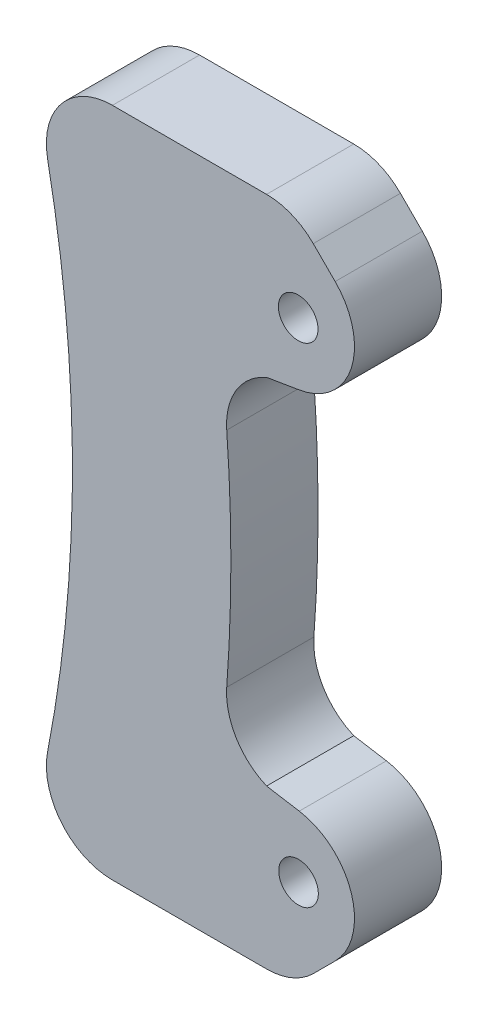
SolidWorks part; units mm, degrees
ref_plane "Front Plane" through (0, 0, 0) normal (0, 0, 1) x (1, 0, 0)
ref_plane "Top Plane" through (0, 0, 0) normal (0, 1, 0) x (1, 0, 0)
ref_plane "Right Plane" through (0, 0, 0) normal (1, 0, 0) x (0, 0, -1)
sketch "Model" plane through (0, 0, 0) normal (0, 0, 1) x (1, 0, 0)
  line L0 (0.4035, -13.81) -> (-2.0711, -13.4)
  line L1 (1.4645, -23.9355) -> (3.1217, -22.2783)
  line L2 (3.1217, 22.2783) -> (1.4645, 23.9355)
  line L3 (-2.0711, 13.4) -> (0.4035, 13.81)
  line L4 (-13.744, -25.4) -> (-2.0711, -25.4)
  line L5 (-2.0711, 25.4) -> (-13.744, 25.4)
  circle A0 centre (0.325, 18.5) radius 1.5
  circle A1 centre (0.3485, -18.5) radius 1.5
  arc A2 (-2.0711, 13.4) -> (-5.0872, 8.4333) centre (-0.101, 8.8045) ccw
  arc A3 (-5.0872, -8.4333) -> (-5.0872, 8.4333) centre (-118.3738, 0) ccw
  arc A4 (-5.0872, -8.4333) -> (-2.0711, -13.4) centre (-0.101, -8.8045) ccw
  arc A5 (3.1217, -22.2783) -> (0.4035, -13.81) centre (-0.4138, -18.7427) ccw
  arc A6 (-2.0711, -25.4) -> (1.4645, -23.9355) centre (-2.0711, -20.4) ccw
  arc A7 (-18.6515, -19.4432) -> (-13.744, -25.4) centre (-13.744, -20.4) ccw
  arc A8 (-18.6515, -19.4432) -> (-18.6515, 19.4432) centre (-118.3738, 0) ccw
  arc A9 (-13.744, 25.4) -> (-18.6515, 19.4432) centre (-13.744, 20.4) ccw
  arc A10 (1.4645, 23.9355) -> (-2.0711, 25.4) centre (-2.0711, 20.4) ccw
  arc A11 (0.4035, 13.81) -> (3.1217, 22.2783) centre (-0.4138, 18.7427) ccw
extrude "Boss-Extrude1" add sketch "Model" along normal blind 6.6
